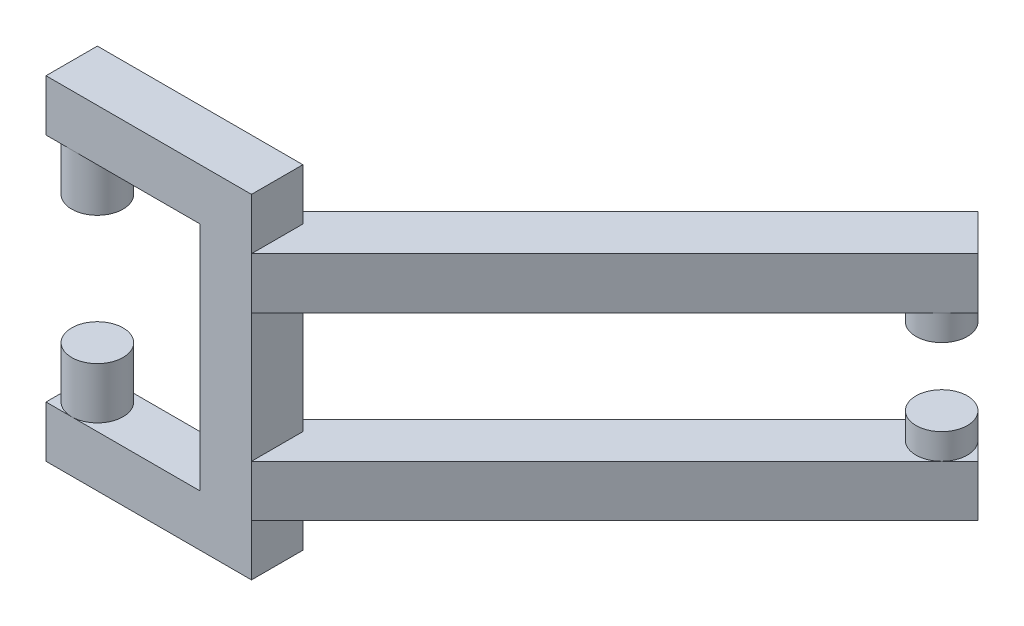
SolidWorks part; units mm, degrees
ref_plane "Alzado" through (0, 0, 0) normal (0, 0, 1) x (1, 0, 0)
ref_plane "Planta" through (0, 0, 0) normal (0, 1, 0) x (1, 0, 0)
ref_plane "Vista lateral" through (0, 0, 0) normal (1, 0, 0) x (0, 0, -1)
sketch "Croquis1" plane through (0, 0, 0) normal (0, 0, 1) x (1, 0, 0)
  line L0 (0, 0) -> (40, 0)
  line L1 (40, 0) -> (40, -65)
  line L2 (40, -65) -> (0, -65)
  line L3 (0, -65) -> (0, -55)
  line L4 (0, -55) -> (30, -55)
  line L5 (30, -55) -> (30, -10)
  line L6 (30, -10) -> (0, -10)
  line L7 (0, -10) -> (0, 0)
  point P3 (40, -32.5)
  point P10 (15, -10)
  dimension "D1" = 40
  dimension "D2" = 40
  dimension "D3" = 10
  dimension "D4" = 10
  dimension "D5" = 10
  dimension "D6" = 45
extrude "Saliente-Extruir1" add sketch "Croquis1" along normal blind 10
sketch "Croquis2" plane through (0, -10, 0) normal (0, -1, 0) x (1, 0, 0)
  circle A0 centre (5, 5) radius 5
  dimension "D1" = 10
  dimension "D2" = 5
  dimension "D3" = 5
extrude "Saliente-Extruir4" add sketch "Croquis2" along normal blind 10 contours A0
sketch "Croquis4" plane through (0, -55, 0) normal (0, 1, 0) x (1, 0, 0)
  circle A0 centre (5, -5) radius 5
  point P2 (5.7985, -5)
  point P4 (0, 0)
  dimension "D3" = 10
  dimension "D1" = 5
  dimension "D2" = 5
extrude "Saliente-Extruir5" add sketch "Croquis4" along normal blind 10
sketch "Croquis6" plane through (40, 0, 0) normal (1, 0, 0) x (0, 0, -1)
  line L0 (-10, -65) -> (-10, 0) construction
  line L1 (-10, -50) -> (90, -50)
  line L2 (-10, -50) -> (-10, -40)
  line L3 (-10, -40) -> (90, -40)
  line L4 (90, -50) -> (90, -40)
  line L6 (-10, -20) -> (90, -20)
  line L7 (-10, -20) -> (-10, -10)
  line L8 (-10, -10) -> (90, -10)
  line L9 (90, -20) -> (90, -10)
  dimension "D1" = 10
  dimension "D2" = 10
  dimension "D3" = 40
  dimension "D4" = 100
  dimension "D5" = 100
  dimension "D6" = 10
sketch "Croquis7" plane through (0, 0, 0) normal (0, 1, 0) x (1, 0, 0)
  line L0 (30, -5.8579) -> (103.6396, 67.7817)
  line L2 (110.7107, 60.7107) -> (40, -10)
  line L4 (0, -10) -> (40, -10) construction
  line L7 (40, -10) -> (40, 0) construction
  line L8 (30, -10) -> (30, -5.8579) construction
  line L10 (103.6396, 67.7817) -> (110.7107, 60.7107)
  line L11 (40, -10) -> (30, -10)
  line L12 (30, -10) -> (30, -5.8579)
  line L13 (30, -4.8121) -> (30, 25.1261) construction
  dimension "D1" = 10
  dimension "D2" = 45
  dimension "D3" = 100
  dimension "D4" = 10
extrude "Saliente-Extruir7" add sketch "Croquis7" against normal blind 10 from offset 10 contours L11 L2 L10 L0 offset against normal yes
ref_plane "Plano1" through (0, -32.5, 0) normal (0, 1, 0) x (1, 0, 0)
mirror "Simetría1" about plane through (0, -32.5, 0) normal (0, 1, 0) of "Saliente-Extruir7"
sketch "Croquis8" plane through (0, -20, 0) normal (0, -1, 0) x (1, 0, 0)
  line L0 (35.8579, 0) -> (103.6396, -67.7817) construction
  line L1 (103.6396, -67.7817) -> (110.7107, -60.7107) construction
  circle A0 centre (103.6396, -60.7107) radius 5
  dimension "D1" = 10
  dimension "D2" = 5
  dimension "D3" = 5
extrude "Saliente-Extruir8" add sketch "Croquis8" along normal blind 5
sketch "Croquis10" plane through (0, -45, 0) normal (0, 1, 0) x (1, 0, 0)
  line L0 (35.8579, 0) -> (103.6396, 67.7817) construction
  line L1 (103.6396, 67.7817) -> (110.7107, 60.7107) construction
  circle A0 centre (103.6396, 60.7107) radius 5
  dimension "D1" = 10
  dimension "D2" = 5
  dimension "D3" = 5
extrude "Saliente-Extruir9" add sketch "Croquis10" along normal blind 5
